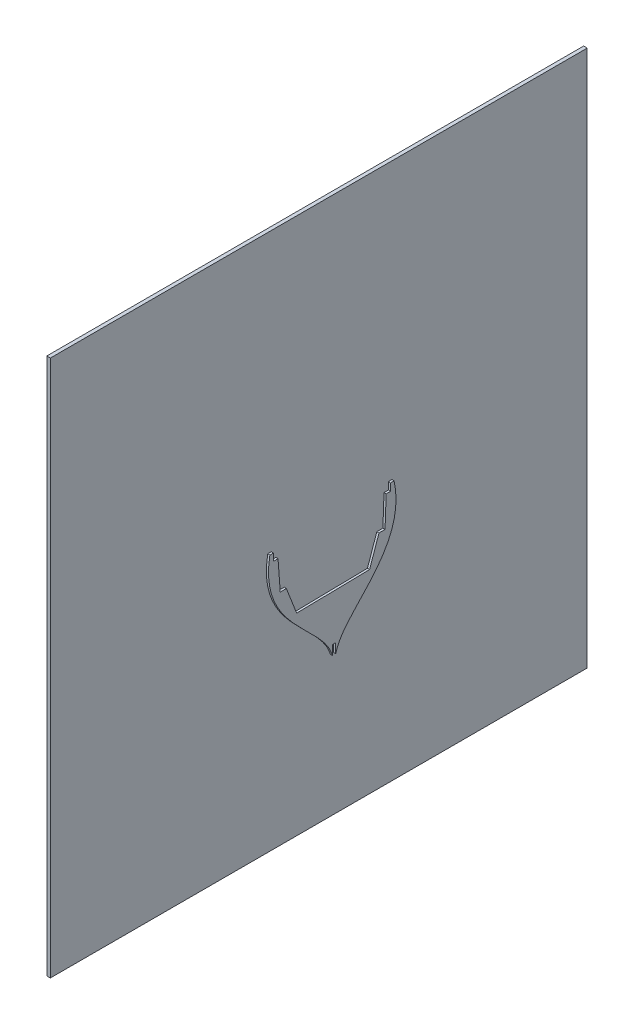
SolidWorks part; units mm, degrees
ref_plane "Plan de face" through (0, 0, 0) normal (0, 0, 1) x (1, 0, 0)
ref_plane "Plan de dessus" through (0, 0, 0) normal (0, 1, 0) x (1, 0, 0)
ref_plane "Plan de droite" through (0, 0, 0) normal (1, 0, 0) x (0, 0, -1)
sketch "Esquisse1" plane through (0, 0, 0) normal (0, 0, 1) x (1, 0, 0)
  point P0 (-20, 0)
  dimension "D1" = 20
sketch3d "Esquisse3D1"
  line L1 (-20, 1121.2893, 777.275) -> (-20, 1121.2893, -722.725)
  line L2 (-20, 1121.2893, 777.275) -> (-20, -378.7107, 777.275)
  line L3 (-20, -378.7107, 777.275) -> (-20, -378.7107, -722.725)
  line L4 (-20, 1121.2893, -722.725) -> (-20, -378.7107, -722.725)
  dimension "D1" = 1500
  dimension "D2" = 1500
extrude "Boss.-Extru.2" add sketch "Esquisse3D1" along direction (1, 0, 0) on the side of the normal blind 10 contours L2 L1 L4 L3
sketch "Esquisse4" plane through (-10, 0, 0) normal (1, 0, 0) x (0, 0, -1)
  line L0 (0, 0) -> (-7.701, 425.1082) construction
  line L1 (169.3944, 339.9131) -> (-188.5193, 333.4294) construction
  line L2 (-187.2006, 249.23) -> (169.0622, 255.6839) construction
  line L3 (-144.268, 175.2448) -> (126.4811, 180.1495) construction
sketch "Esquisse5" plane through (0, 0, 0) normal (1, 0, 0) x (0, 0, -1)
  line L0 (-7.701, 425.1082) -> (0, 0) construction
  line L2 (0, 0) -> (5.7869, 40.7896) construction
  line L3 (5.7869, 40.7896) -> (8.0685, 109.6702) construction
  line L4 (8.0685, 109.6702) -> (209.7955, 165.586) construction
  line L5 (209.7955, 165.586) -> (167.0398, 360.1691) construction
  line L8 (167.0398, 360.1691) -> (157.0398, 359.9879)
  line L9 (157.0398, 359.9879) -> (157.2145, 339.6925)
  line L10 (169.3944, 339.9131) -> (-188.5193, 333.4294) construction
  line L11 (157.2145, 339.6925) -> (144.9235, 339.4698)
  line L12 (144.9235, 339.4698) -> (141.826, 255.1905)
  line L13 (-187.2006, 249.23) -> (169.0622, 255.6839) construction
  line L14 (141.826, 255.1905) -> (124.8476, 254.8829)
  line L15 (124.8476, 254.8829) -> (98.6917, 179.6461)
  line L16 (-144.268, 175.2448) -> (126.4811, 180.1495) construction
  line L17 (98.6917, 179.6461) -> (-105.1335, 175.9537)
  line L18 (0, 0) -> (-7.2604, 40.5532) construction
  line L19 (-7.2604, 40.5532) -> (-12.0354, 109.306) construction
  line L20 (-12.0354, 109.306) -> (-215.6552, 157.8788) construction
  line L21 (-215.6552, 157.8788) -> (-179.9751, 353.8828) construction
  line L22 (-133.9972, 250.1938) -> (-105.1335, 175.9537)
  line L23 (-150.9756, 249.8863) -> (-133.9972, 250.1938)
  line L24 (-157.1236, 333.9981) -> (-150.9756, 249.8863)
  line L25 (-169.4146, 333.7755) -> (-157.1236, 333.9981)
  line L26 (-169.9751, 354.0639) -> (-169.4146, 333.7755)
  line L27 (-179.9751, 353.8828) -> (-169.9751, 354.0639)
  spline S0 degree 4 poles (0, 0) (5.7869, 40.7896) (8.0685, 109.6702) (209.7955, 165.586) (167.0398, 360.1691) knots 0 0 0 0 0 1 1 1 1 1
  spline S1 degree 4 poles (0, 0) (-7.2604, 40.5532) (-12.0354, 109.306) (-215.6552, 157.8788) (-179.9751, 353.8828) knots 0 0 0 0 0 1 1 1 1 1
  point P30 (-3.2209, 177.7999)
  dimension "D1" = 10
extrude "Boss.-Extru.3" add sketch "Esquisse5" along normal blind 6 separate body
sketch "Esquisse6" plane through (6, 0, 0) normal (1, 0, 0) x (0, 0, -1)
  line L0 (-4.9171, 22.9431) -> (-5.4062, 49.9431)
  line L1 (-5.4062, 49.9431) -> (3.5938, 50.1062)
  line L2 (3.5938, 50.1062) -> (4.0829, 23.1062)
  line L3 (4.0829, 23.1062) -> (117.0633, -47.527)
  line L4 (117.0633, -47.527) -> (-85.2277, -65.22)
  line L5 (-85.2277, -65.22) -> (-4.9171, 22.9431)
  line L6 (-4.9171, 22.9431) -> (4.0829, 23.1062) construction
  line L7 (-144.268, 175.2448) -> (126.4811, 180.1495) construction
  spline S0 degree 4 poles (-179.9751, 353.8828) (-215.6552, 157.8788) (-12.0354, 109.306) (-7.2604, 40.5532) (0, 0) knots 0 0 0 0 0 1 1 1 1 1 construction
  spline S1 degree 4 poles (0, 0) (5.7869, 40.7896) (8.0685, 109.6702) (209.7955, 165.586) (167.0398, 360.1691) knots 0 0 0 0 0 1 1 1 1 1 construction
  dimension "D1" = 9
  dimension "D2" = 27
extrude "Enlèv. mat.-Extru.1" cut sketch "Esquisse6" against normal blind 6
